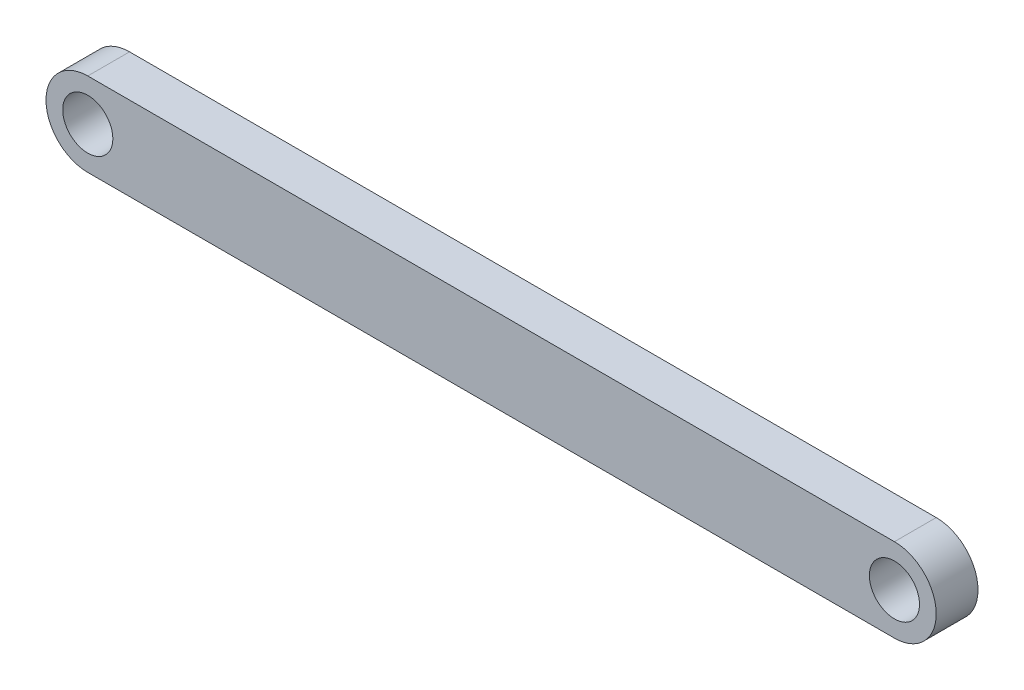
SolidWorks part; units mm, degrees
ref_plane "Plano frontal" through (0, 0, 0) normal (0, 0, 1) x (1, 0, 0)
ref_plane "Plano superior" through (0, 0, 0) normal (0, 1, 0) x (1, 0, 0)
ref_plane "Plano direito" through (0, 0, 0) normal (1, 0, 0) x (0, 0, -1)
sketch "Esboço1" plane through (0, 0, 0) normal (0, 0, 1) x (1, 0, 0)
  line L0 (-48.27, 5) -> (48.27, 5)
  line L1 (-98.54, 0) -> (98.54, 0) construction
  line L2 (-48.27, -5) -> (48.27, -5)
  arc A0 (-48.27, 5) -> (-48.27, -5) centre (-48.27, 0) ccw
  arc A1 (48.27, 5) -> (48.27, -5) centre (48.27, 0) cw
  circle A4 centre (-48.27, 0) radius 3
  circle A5 centre (48.27, 0) radius 3
  point P3 (0, 5)
  dimension "D3" = 6
  dimension "D4" = 6
  dimension "D1" = 96.54
  dimension "D2" = 5
extrude "Ressalto-extrusão1" add sketch "Esboço1" along normal blind 5
